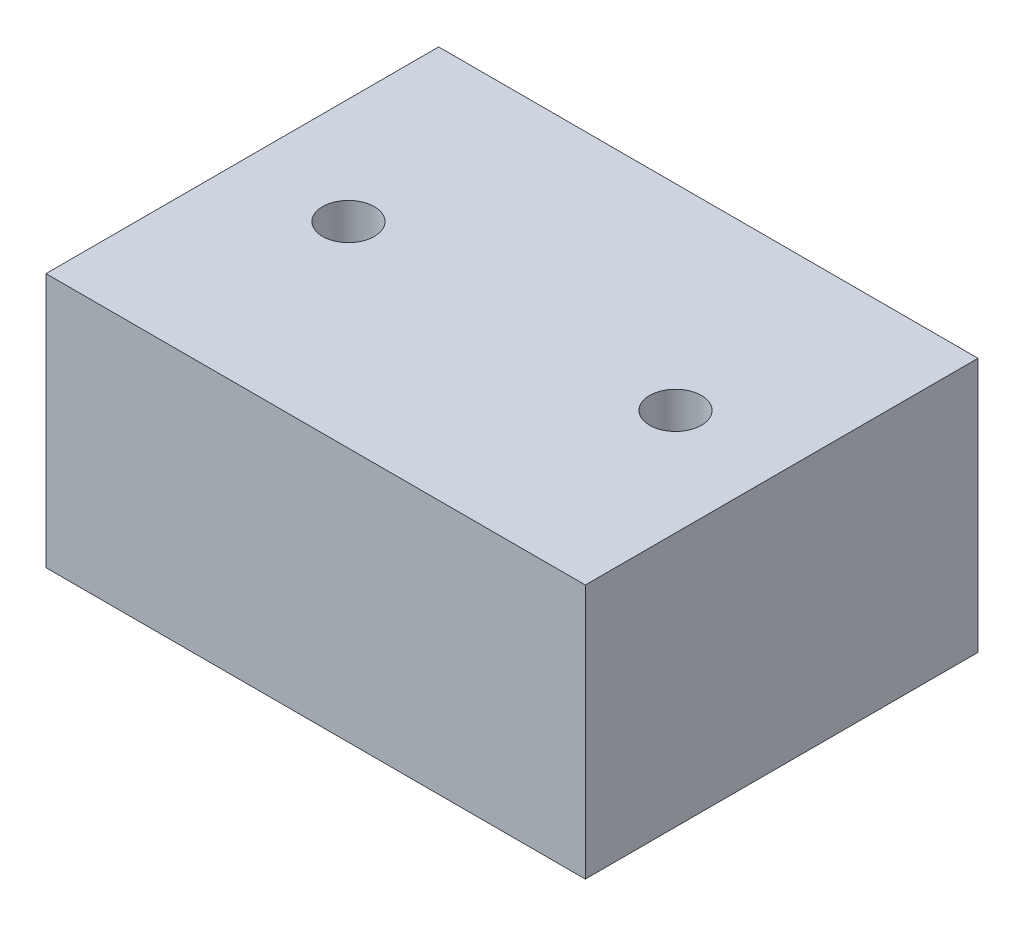
SolidWorks part; units mm, degrees
ref_plane "Front Plane" through (0, 0, 0) normal (0, 0, 1) x (1, 0, 0)
ref_plane "Top Plane" through (0, 0, 0) normal (0, 1, 0) x (1, 0, 0)
ref_plane "Right Plane" through (0, 0, 0) normal (1, 0, 0) x (0, 0, -1)
sketch "Sketch1" plane through (0, 0, 0) normal (0, 1, 0) x (1, 0, 0)
  line L1 (0, 0) -> (25.41, 0)
  line L2 (0, 0) -> (0, 18.5)
  line L3 (0, 18.5) -> (25.41, 18.5)
  line L4 (25.41, 0) -> (25.41, 18.5)
extrude "Boss-Extrude1" add sketch "Sketch1" along normal blind 12
sketch "Sketch2" plane through (0, 0, 0) normal (0, -1, 0) x (1, 0, 0)
  line L0 (0, 0) -> (1.5, 0)
  line L1 (0, 0) -> (25.41, 0) construction
  line L2 (1.5, 0) -> (1.5, -18.5)
  line L3 (25.41, -18.5) -> (0, -18.5) construction
  line L4 (25.41, 0) -> (23.91, 0)
  line L5 (23.91, 0) -> (23.91, -18.5)
  line L6 (0, 0) -> (0, -1.5)
  line L7 (0, -18.5) -> (0, 0) construction
  line L8 (0, -1.5) -> (25.41, -1.5)
  line L9 (25.41, 0) -> (25.41, -18.5) construction
  line L10 (0, -18.5) -> (0, -17)
  line L11 (0, -17) -> (25.41, -17)
hole_wizard "#2-56 Tapped Hole1" positions "Sketch3" profile "Sketch4" tap size "#2-56" standard "ANSI Inch"
sketch "Sketch3" plane through (0, 0, 0) normal (0, -1, 0) x (-1, 0, 0)
  line L0 (-23.91, 0) -> (-23.91, 18.5) construction
  line L1 (0, 17) -> (-25.41, 17) construction
  line L2 (0, 1.5) -> (-25.41, 1.5) construction
  line L3 (-1.5, 0) -> (-1.5, 18.5) construction
  point P0 (-23.91, 17)
  point P6 (-23.91, 1.5)
  point P10 (-1.5, 1.5)
  point P14 (-1.5, 17)
sketch "Sketch4" plane through (23.91, 0, -17) normal (1, 0, 0) x (0, 0, -1)
  line L0 (0, 0) -> (0, 8)
  line L1 (0, 8) -> (0.889, 7.4658)
  line L2 (0.889, 7.4658) -> (0.889, 0)
  line L5 (0.889, 0) -> (0, 0)
  line L10 (0, 8) -> (-0.889, 7.4658) construction
  line L11 (0, -6.35) -> (0, 107.95) construction
  dimension "Tap Drill Dia." = 1.778
  dimension "Tap Drill Depth" = 8
  dimension "Drill Angle" = 118
cosmetic thread "Hole Thread1"
cosmetic thread "Hole Thread2"
cosmetic thread "Hole Thread3"
cosmetic thread "Hole Thread4"
sketch "Sketch5" plane through (0, 0, 0) normal (0, -1, 0) x (1, 0, 0)
  circle A0 centre (12.705, -9.25) radius 3
extrude "Cut-Extrude1" cut sketch "Sketch5" against normal blind 3
sketch "Sketch6" plane through (0, 0, 0) normal (0, -1, 0) x (1, 0, 0)
  line L0 (0, -9.25) -> (25.41, -9.25)
  line L1 (0, -18.5) -> (0, 0) construction
  line L2 (25.41, 0) -> (25.41, -18.5) construction
  line L3 (0, -9.25) -> (5, -9.25)
  line L4 (25.41, -9.25) -> (20.41, -9.25)
hole_wizard "CBORE for #2 Binding Head Machine Screw2" positions "Sketch9" profile "Sketch10" counterbore size "#2" standard "ANSI Inch" end condition through all
sketch "Sketch9" plane through (0, 0, 0) normal (0, -1, 0) x (-1, 0, 0)
  point P0 (-20.41, 9.25)
  point P3 (-5, 9.25)
sketch "Sketch10" plane through (20.41, 0, -9.25) normal (1, 0, 0) x (0, 0, -1)
  line L0 (0, 0) -> (0, 12)
  line L1 (0, 12) -> (1.2192, 12)
  line L3 (1.2192, 12) -> (1.2192, 7.27)
  line L4 (1.2192, 7.27) -> (2.7788, 7.27)
  line L5 (2.7788, 7.27) -> (2.7788, 0)
  line L7 (2.7788, 0) -> (0, 0)
  line L11 (0, -6.35) -> (0, 107.95) construction
  dimension "Thru Hole Dia." = 2.4384
  dimension "Thru Hole Depth" = 12
  dimension "C'Bore Dia." = 5.5575
  dimension "C'Bore Depth" = 7.27
